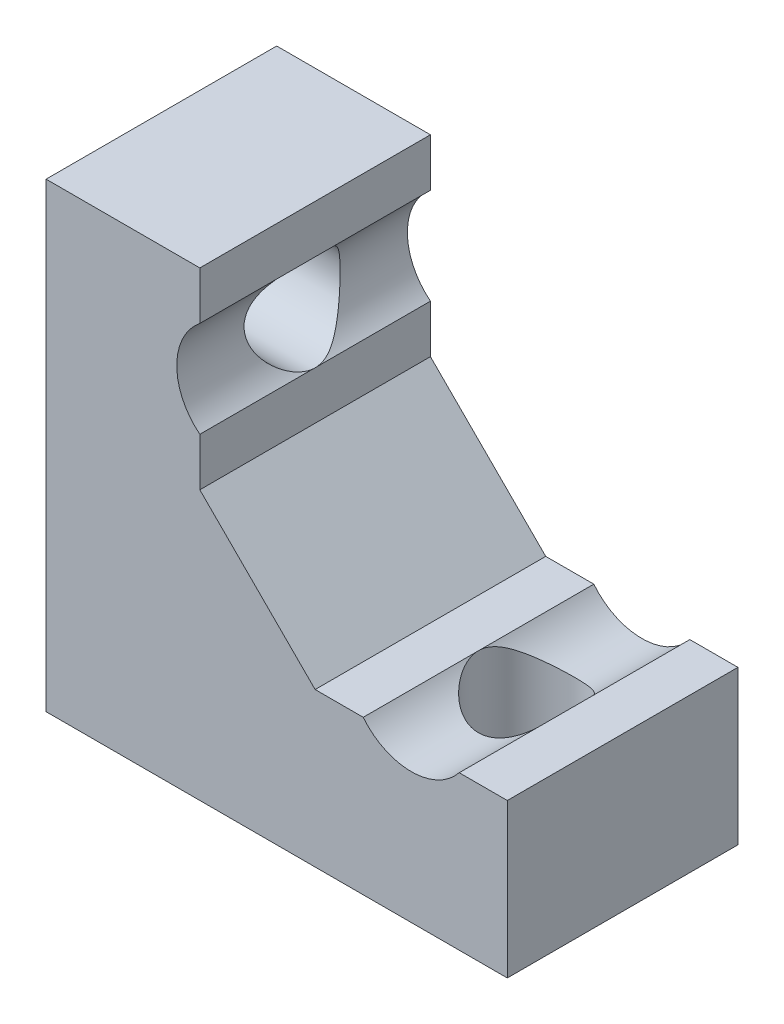
SolidWorks part; units mm, degrees
material "Aleación 1060"
ref_plane "Alzado" through (0, 0, 0) normal (0, 0, 1) x (1, 0, 0)
ref_plane "Planta" through (0, 0, 0) normal (0, 1, 0) x (1, 0, 0)
ref_plane "Vista lateral" through (0, 0, 0) normal (1, 0, 0) x (0, 0, -1)
sketch "Croquis1" plane through (0, 0, 0) normal (0, 0, 1) x (1, 0, 0)
  line L0 (0, 0) -> (0, 12)
  line L1 (0, 0) -> (12, 0)
  line L2 (0, 12) -> (4, 12)
  line L3 (12, 0) -> (12, 4)
  line L4 (4, 12) -> (4, 7)
  line L5 (12, 4) -> (7, 4)
  line L6 (4, 7) -> (7, 4)
  dimension "D1" = 12
  dimension "D2" = 12
  dimension "D3" = 4
  dimension "D4" = 4
  dimension "D5" = 5
  dimension "D6" = 5
extrude "Saliente-Extruir1" add sketch "Croquis1" along normal blind 6
sketch "Croquis3" plane through (0, 4, 0) normal (0, 1, 0) x (1, 0, 0)
  line L0 (12, -6) -> (12, 0) construction
  circle A0 centre (9.5, -3) radius 1.25
  point P2 (0, 0)
  point P5 (12, -3)
  dimension "D1" = 2.5
extrude "Cortar-Extruir1" cut sketch "Croquis3" against normal up to vertex (4 mm away)
sketch "Croquis4" plane through (4, 0, 0) normal (1, 0, 0) x (0, 0, -1)
  line L0 (-6, 12) -> (0, 12) construction
  circle A0 centre (-3, 9.5) radius 1.25
  point P2 (0, 0)
  point P5 (-3, 12)
  dimension "D1" = 2.5
extrude "Cortar-Extruir2" cut sketch "Croquis4" against normal up to vertex (4 mm away)
sketch "Croquis5" plane through (0, 0, 6) normal (0, 0, 1) x (1, 0, 0)
  line L0 (12, 4) -> (7, 4) construction
  line L1 (0, 0) -> (11.2603, 11.2603) construction
  circle A0 centre (9.5, 5) radius 1.6
  circle A1 centre (5, 9.5) radius 1.6
  dimension "D1" = 1
  dimension "D2" = 3.2
extrude "Cortar-Extruir3" cut sketch "Croquis5" against normal up to vertex (6 mm away)
